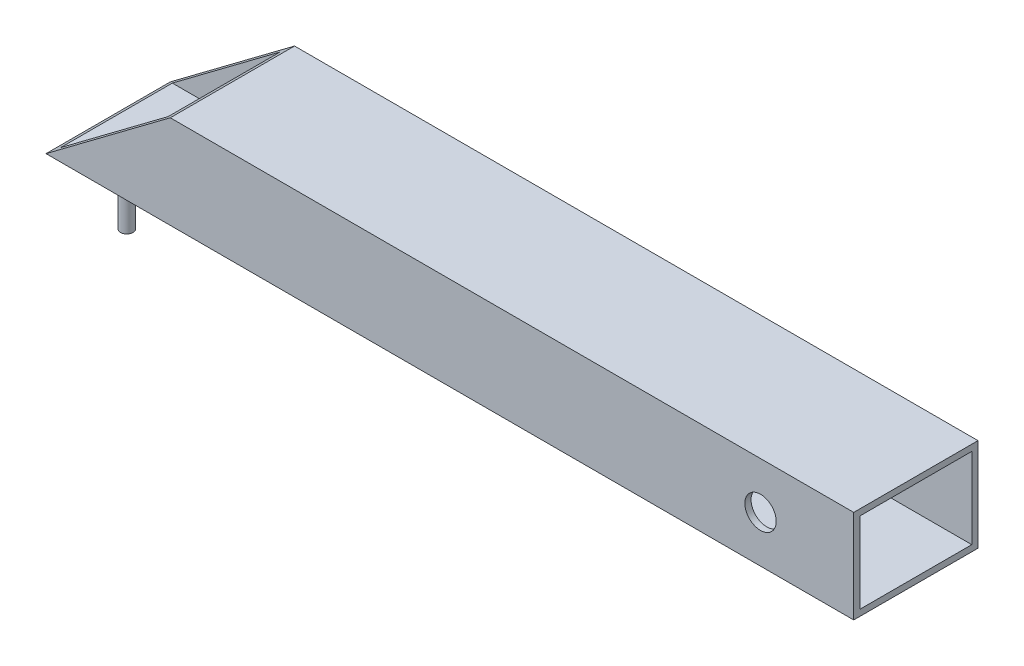
SolidWorks part; units mm, degrees
ref_plane "Plan de face" through (0, 0, 0) normal (0, 0, 1) x (1, 0, 0)
ref_plane "Plan de dessus" through (0, 0, 0) normal (0, 1, 0) x (1, 0, 0)
ref_plane "Plan de droite" through (0, 0, 0) normal (1, 0, 0) x (0, 0, -1)
sketch "Esquisse1" plane through (0, 0, 0) normal (0, 0, 1) x (1, 0, 0)
  line L0 (0, 0) -> (-116.13, 0) construction
  line L1 (15, -7.5) -> (-115, -7.5)
  line L2 (15, -7.5) -> (15, 7.5)
  line L3 (15, 7.5) -> (-95, 7.5)
  line L4 (-95, 7.5) -> (-115, -7.5)
  circle A0 centre (0, 0) radius 2.5246
  dimension "D1" = 15
extrude "Boss.-Extru.1" add sketch "Esquisse1" along normal blind 20
sketch "Esquisse2" plane through (15, 0, 0) normal (1, 0, 0) x (0, 0, -1)
  line L0 (-20, -7.5) -> (-20, 7.5) construction
  line L1 (-19, 6.5) -> (-1, 6.5)
  line L2 (-19, 6.5) -> (-19, -6.5)
  line L3 (-19, -6.5) -> (-1, -6.5)
  line L4 (-1, 6.5) -> (-1, -6.5)
  line L5 (-20, -7.5) -> (0, -7.5) construction
  dimension "D1" = 18
  dimension "D2" = 1
  dimension "D3" = 1
  dimension "D4" = 13
extrude "Enlèv. mat.-Extru.1" cut sketch "Esquisse2" against normal blind 200
sketch "Esquisse4" plane through (0, -7.5, 0) normal (0, -1, 0) x (1, 0, 0)
  line L0 (-115, 10) -> (-105.3748, 10) construction
  line L1 (-115, 20) -> (-115, 0) construction
  line L2 (-115, 20) -> (15, 20) construction
  circle A0 centre (-107, 15) radius 1
  circle A1 centre (-107, 5) radius 1
  dimension "D2" = 5
  dimension "D3" = 5
  dimension "D4" = 8
  dimension "D5" = 8
  dimension "D1" = 10
extrude "Boss.-Extru.2" add sketch "Esquisse4" along normal blind 9
sketch "Esquisse5" plane through (0, 0, 0) normal (0, 0, -1) x (-1, 0, 0)
  circle A0 centre (0, 0) radius 2.5
extrude "Boss.-Extru.3" add sketch "Esquisse5" along normal blind 2 separate body
